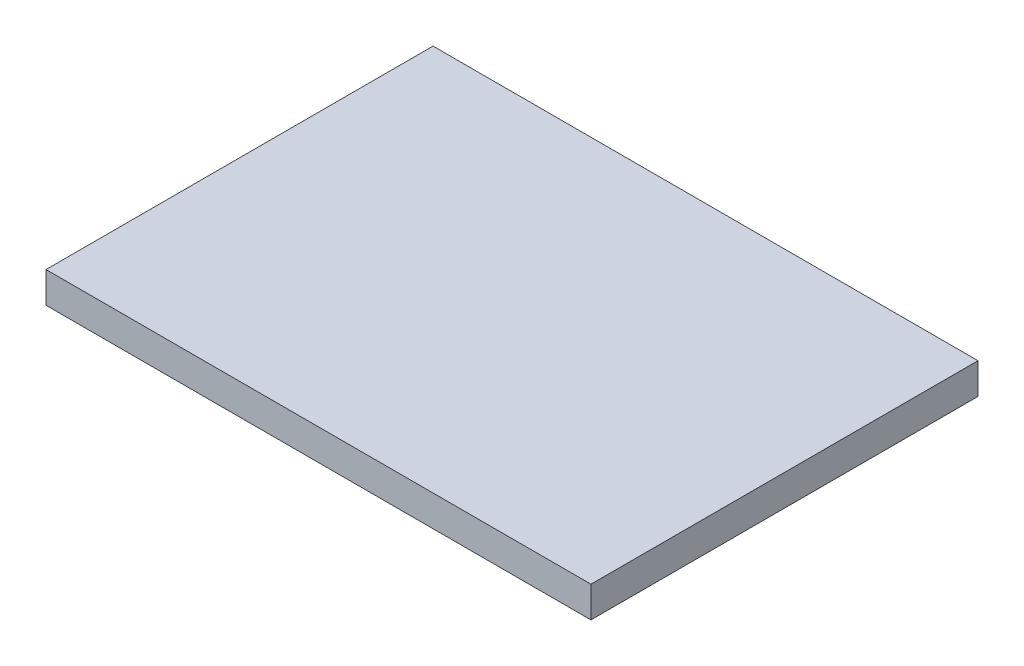
SolidWorks part; units mm, degrees
material "AISI 316 Stainless Steel Sheet (SS)"
ref_plane "Front Plane" through (0, 0, 0) normal (0, 0, 1) x (1, 0, 0)
ref_plane "Top Plane" through (0, 0, 0) normal (0, 1, 0) x (1, 0, 0)
ref_plane "Right Plane" through (0, 0, 0) normal (1, 0, 0) x (0, 0, -1)
sketch "Sketch1" plane through (0, 0, 0) normal (0, 1, 0) x (1, 0, 0)
  line L1 (-17.6, -12.5) -> (17.6, -12.5)
  line L2 (-17.6, -12.5) -> (-17.6, 12.5)
  line L3 (-17.6, 12.5) -> (17.6, 12.5)
  line L4 (17.6, -12.5) -> (17.6, 12.5)
  line L5 (-17.6, -12.5) -> (17.6, 12.5) construction
  line L6 (-17.6, 12.5) -> (17.6, -12.5) construction
  point P0 (0, 0)
  dimension "D1" = 35.2
  dimension "D2" = 25
extrude "Boss-Extrude1" add sketch "Sketch1" along normal blind 2
